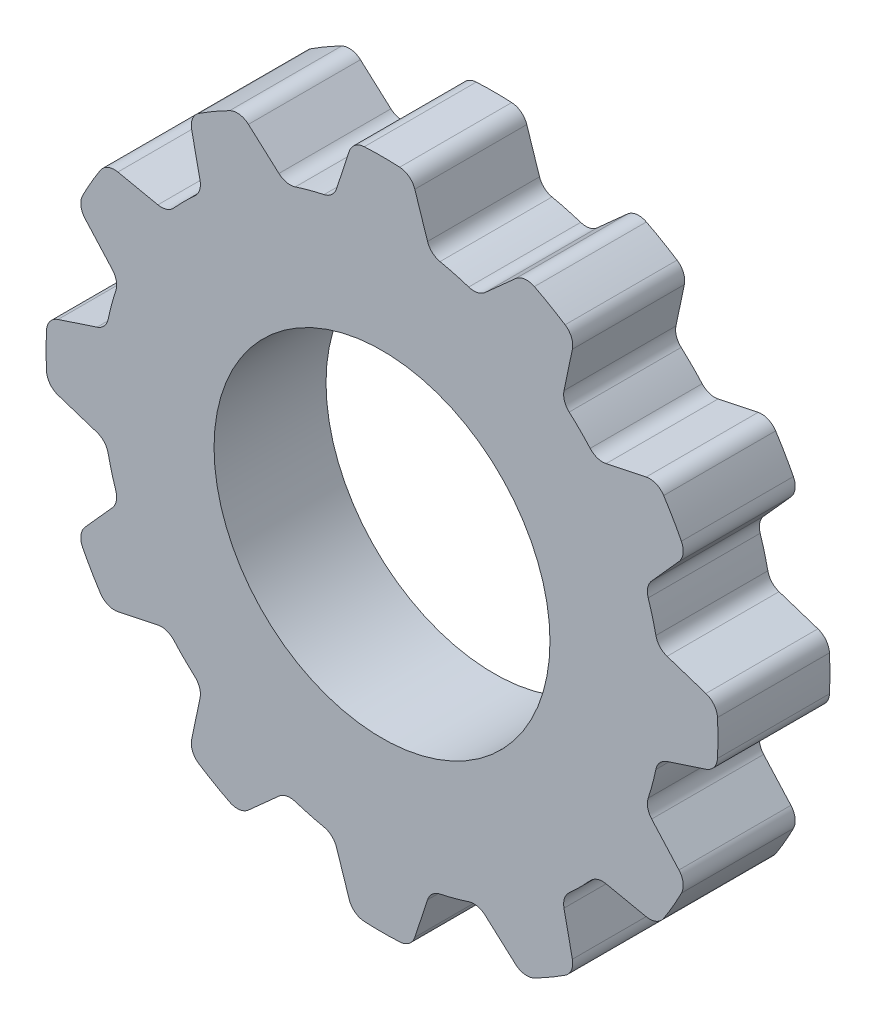
SolidWorks part; units mm, degrees
ref_plane "Front Plane" through (0, 0, 0) normal (0, 0, 1) x (1, 0, 0)
ref_plane "Top Plane" through (0, 0, 0) normal (0, 1, 0) x (1, 0, 0)
ref_plane "Right Plane" through (0, 0, 0) normal (1, 0, 0) x (0, 0, -1)
sketch "Sketch1" plane through (0, 0, 0) normal (0, 0, 1) x (1, 0, 0)
  line L1 (0, 0) -> (-50, 0) construction
  line L2 (-5.2293, 59.7717) -> (-8.6824, 49.2404)
  line L3 (-5.2293, 59.7717) -> (-8.6824, 49.2404)
  line L4 (8.6824, 49.2404) -> (5.2293, 59.7717)
  line L5 (25.3571, 54.3785) -> (17.101, 46.9846)
  line L6 (32.1394, 38.3022) -> (34.4146, 49.1491)
  line L7 (-17.101, 46.9846) -> (-25.3571, 54.3785)
  line L8 (49.1491, 34.4146) -> (38.3022, 32.1394)
  line L9 (46.9846, 17.101) -> (54.3785, 25.3571)
  line L10 (59.7717, 5.2293) -> (49.2404, 8.6824)
  line L11 (-34.4146, 49.1491) -> (-32.1394, 38.3022)
  line L12 (49.2404, -8.6824) -> (59.7717, -5.2293)
  line L13 (54.3785, -25.3571) -> (46.9846, -17.101)
  line L14 (38.3022, -32.1394) -> (49.1491, -34.4146)
  line L15 (34.4146, -49.1491) -> (32.1394, -38.3022)
  line L16 (17.101, -46.9846) -> (25.3571, -54.3785)
  line L17 (5.2293, -59.7717) -> (8.6824, -49.2404)
  line L18 (-8.6824, -49.2404) -> (-5.2293, -59.7717)
  line L19 (-25.3571, -54.3785) -> (-17.101, -46.9846)
  line L20 (-32.1394, -38.3022) -> (-34.4146, -49.1491)
  line L21 (-49.1491, -34.4146) -> (-38.3022, -32.1394)
  line L22 (-46.9846, -17.101) -> (-54.3785, -25.3571)
  line L23 (-59.7717, -5.2293) -> (-49.2404, -8.6824)
  line L24 (-49.2404, 8.6824) -> (-59.7717, 5.2293)
  line L25 (-54.3785, 25.3571) -> (-46.9846, 17.101)
  line L26 (-38.3022, 32.1394) -> (-49.1491, 34.4146)
  arc A0 (0, 60) -> (-5.2293, 59.7717) centre (0, 0) ccw
  circle A1 centre (0, 0) radius 30
  arc A2 (-46.9846, 17.101) -> (-49.2404, 8.6824) centre (0, 0) ccw
  arc A3 (-25.3571, 54.3785) -> (-34.4146, 49.1491) centre (0, 0) ccw
  arc A4 (5.2293, 59.7717) -> (-5.2293, 59.7717) centre (0, 0) ccw
  arc A5 (34.4146, 49.1491) -> (25.3571, 54.3785) centre (0, 0) ccw
  arc A6 (54.3785, 25.3571) -> (49.1491, 34.4146) centre (0, 0) ccw
  arc A7 (59.7717, -5.2293) -> (59.7717, 5.2293) centre (0, 0) ccw
  arc A8 (49.1491, -34.4146) -> (54.3785, -25.3571) centre (0, 0) ccw
  arc A9 (25.3571, -54.3785) -> (34.4146, -49.1491) centre (0, 0) ccw
  arc A10 (-5.2293, -59.7717) -> (5.2293, -59.7717) centre (0, 0) ccw
  arc A11 (-34.4146, -49.1491) -> (-25.3571, -54.3785) centre (0, 0) ccw
  arc A12 (-54.3785, -25.3571) -> (-49.1491, -34.4146) centre (0, 0) ccw
  arc A13 (-59.7717, 5.2293) -> (-59.7717, -5.2293) centre (0, 0) ccw
  arc A14 (-49.1491, 34.4146) -> (-54.3785, 25.3571) centre (0, 0) ccw
  arc A15 (-49.2404, -8.6824) -> (-46.9846, -17.101) centre (0, 0) ccw
  arc A16 (-38.3022, -32.1394) -> (-32.1394, -38.3022) centre (0, 0) ccw
  arc A17 (-17.101, -46.9846) -> (-8.6824, -49.2404) centre (0, 0) ccw
  arc A18 (8.6824, -49.2404) -> (17.101, -46.9846) centre (0, 0) ccw
  arc A19 (32.1394, -38.3022) -> (38.3022, -32.1394) centre (0, 0) ccw
  arc A20 (46.9846, -17.101) -> (49.2404, -8.6824) centre (0, 0) ccw
  arc A21 (49.2404, 8.6824) -> (46.9846, 17.101) centre (0, 0) ccw
  arc A22 (38.3022, 32.1394) -> (32.1394, 38.3022) centre (0, 0) ccw
  arc A23 (17.101, 46.9846) -> (8.6824, 49.2404) centre (0, 0) ccw
  arc A24 (-8.6824, 49.2404) -> (-17.101, 46.9846) centre (0, 0) ccw
  arc A25 (-32.1394, 38.3022) -> (-38.3022, 32.1394) centre (0, 0) ccw
  point P60 (0, 0)
  dimension "D1" = 120
  dimension "D2" = 60
  dimension "D3" = 12
extrude "Boss-Extrude1" add sketch "Sketch1" along normal blind 20 contours L11 A25 L26 A14 L25 A2 L24 A13 L23 A15 L22 A12 L21 A16 L20 A11 L19 A17 L18 A10 L17 A18 L16 A9 L15 A19 L14 A8 L13 A20 L12 A7 L10 A21 L9 A6 L8 A22 L6 A5 L5 A23 L4 A4 A0 L2 A24 L7 A3 A1
fillet "Fillet1" radius 3 48 edges at (32.1394, 38.3022, 10) (38.3022, 32.1394, 10) (49.1491, 34.4146, 10) (54.3785, 25.3571, 10) (46.9846, 17.101, 10) (49.2404, 8.6824, 10) (59.7717, 5.2293, 10) (59.7717, -5.2293, 10) (49.2404, -8.6824, 10) (46.9846, -17.101, 10) (54.3785, -25.3571, 10) (49.1491, -34.4146, 10) (38.3022, -32.1394, 10) (32.1394, -38.3022, 10) (34.4146, -49.1491, 10) (25.3571, -54.3785, 10) (17.101, -46.9846, 10) (8.6824, -49.2404, 10) (5.2293, -59.7717, 10) (-5.2293, -59.7717, 10) (-8.6824, -49.2404, 10) (-17.101, -46.9846, 10) (-25.3571, -54.3785, 10) (-34.4146, -49.1491, 10) (-32.1394, -38.3022, 10) (-38.3022, -32.1394, 10) (-49.1491, -34.4146, 10) (-54.3785, -25.3571, 10) (-46.9846, -17.101, 10) (-49.2404, -8.6824, 10) (-59.7717, -5.2293, 10) (-59.7717, 5.2293, 10) (-49.2404, 8.6824, 10) (-46.9846, 17.101, 10) (-54.3785, 25.3571, 10) (-49.1491, 34.4146, 10) (-38.3022, 32.1394, 10) (-32.1394, 38.3022, 10) (-34.4146, 49.1491, 10) (-25.3571, 54.3785, 10) (-17.101, 46.9846, 10) (-8.6824, 49.2404, 10) (-5.2293, 59.7717, 10) (5.2293, 59.7717, 10) (8.6824, 49.2404, 10) (17.101, 46.9846, 10) (25.3571, 54.3785, 10) (34.4146, 49.1491, 10)
